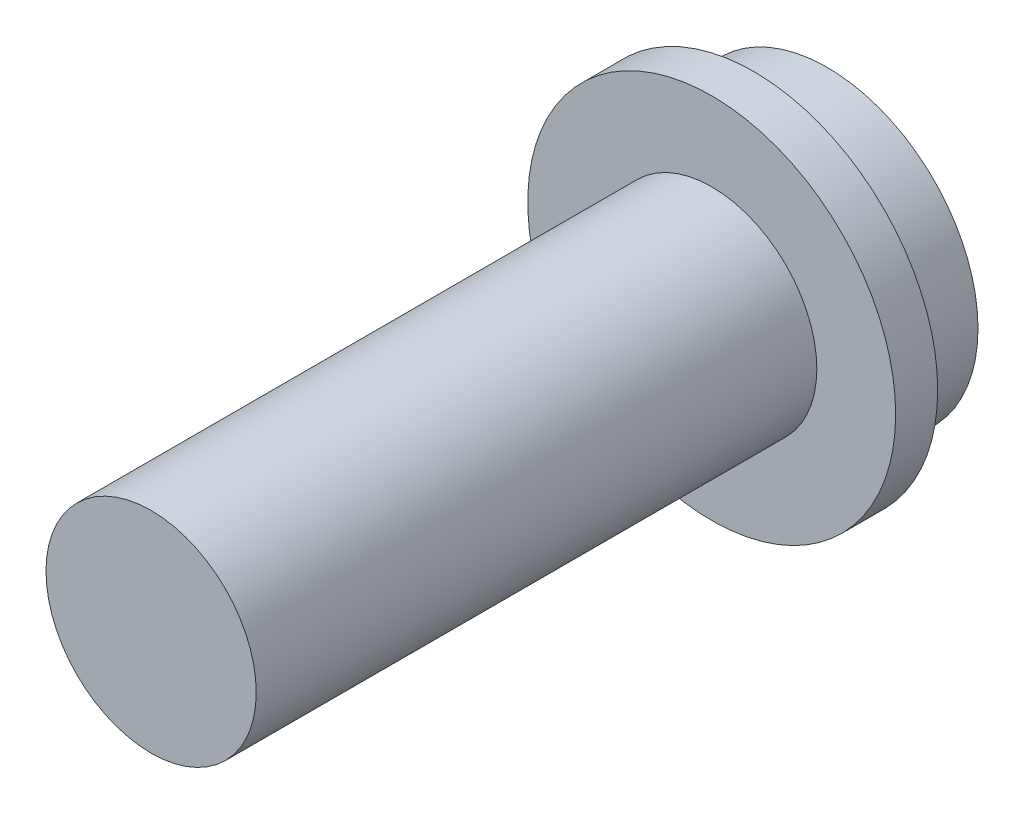
SolidWorks part; units mm, degrees
ref_plane "Front Plane" through (0, 0, 0) normal (0, 0, 1) x (1, 0, 0)
ref_plane "Top Plane" through (0, 0, 0) normal (0, 1, 0) x (1, 0, 0)
ref_plane "Right Plane" through (0, 0, 0) normal (1, 0, 0) x (0, 0, -1)
sketch "S01 - M6 threaded shank" plane through (0, 0, 0) normal (0, 0, 1) x (1, 0, 0)
  circle A0 centre (0, 0) radius 3
  dimension "D1" = 6
extrude "01 - M6 threaded shank" add sketch "S01 - M6 threaded shank" along normal blind 16
sketch "S02 - Button head clearing diameter" plane through (0, 0, 0) normal (0, 0, 1) x (1, 0, 0)
  circle A0 centre (0, 0) radius 5.25
  dimension "D1" = 10.5
extrude "02 - Button head clearing diameter" add sketch "S02 - Button head clearing diameter" along normal blind 1.2 from offset 1.2
sketch "S03 - Button crown" plane through (0, 0, 0) normal (0, 0, 1) x (1, 0, 0)
  circle A0 centre (0, 0) radius 4.3
  dimension "D1" = 8.6
extrude "03 - Button crown" add sketch "S03 - Button crown" along normal blind 2.1 from offset 3.3
sketch "S04 - 4 mm hex socket" plane through (0, 0, 0) normal (0, 0, 1) x (1, 0, 0)
  line L0 (2.3094, 0) -> (1.1547, 2)
  line L1 (1.1547, 2) -> (-1.1547, 2)
  line L2 (-1.1547, 2) -> (-2.3094, 0)
  line L3 (-2.3094, 0) -> (-1.1547, -2)
  line L4 (-1.1547, -2) -> (1.1547, -2)
  line L5 (1.1547, -2) -> (2.3094, 0)
  dimension "D1" = 1.1547
  dimension "D2" = 2.3094
  dimension "D3" = 1.1547
  dimension "D4" = 2.3094
  dimension "D5" = 2
  dimension "D6" = 2
extrude "04 - 4 mm hex socket" cut sketch "S04 - 4 mm hex socket" along normal blind 2.2 from offset 3.4
